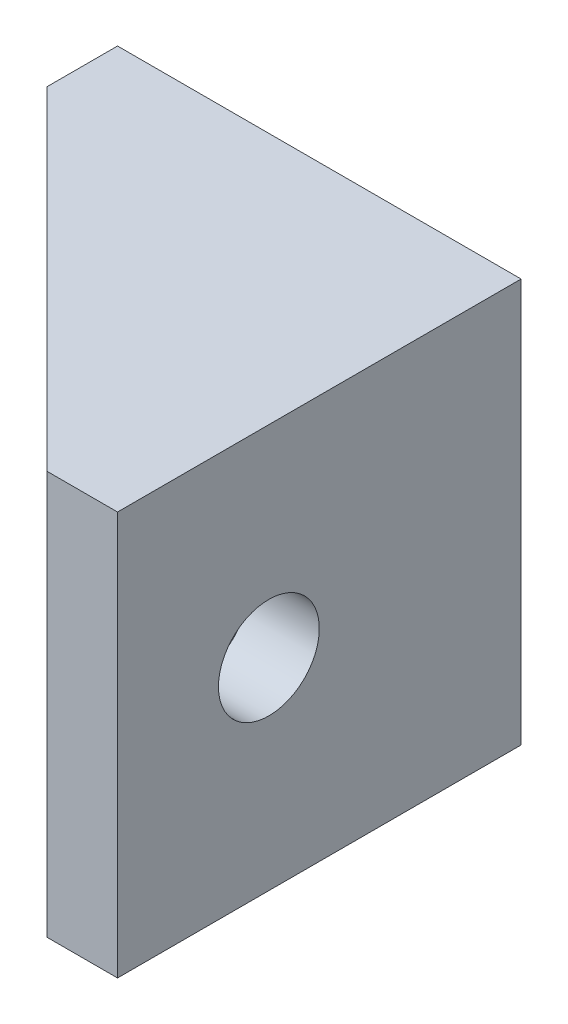
SolidWorks part; units mm, degrees
material "6061 Alloy"
ref_plane "Front Plane" through (0, 0, 0) normal (0, 0, 1) x (1, 0, 0)
ref_plane "Top Plane" through (0, 0, 0) normal (0, 1, 0) x (1, 0, 0)
ref_plane "Right Plane" through (0, 0, 0) normal (1, 0, 0) x (0, 0, -1)
sketch "Sketch1" plane through (0, 0, 0) normal (0, 1, 0) x (1, 0, 0)
  line L1 (-20, 20) -> (0, 20)
  line L2 (-20, 20) -> (-20, 0)
  line L3 (-20, 0) -> (0, 0)
  line L4 (0, 20) -> (0, 0)
  dimension "D1" = 20
extrude "Boss-Extrude1" add sketch "Sketch1" along normal blind 20
sketch "Sketch2" plane through (-20, 0, 0) normal (-1, 0, 0) x (0, 0, 1)
  line L0 (-20, 20) -> (0, 20) construction
  line L1 (-16.5, 18) -> (0, 18)
  line L2 (-16.5, 18) -> (-16.5, 2)
  line L3 (-16.5, 2) -> (0, 2)
  line L4 (0, 18) -> (0, 2)
  line L5 (-20, 0) -> (0, 0) construction
  line L6 (-20, 20) -> (-20, 0) construction
  line L7 (0, 20) -> (0, 0) construction
  dimension "D1" = 2
  dimension "D2" = 2
  dimension "D3" = 3.5
extrude "Cut-Extrude1" cut sketch "Sketch2" against normal blind 16.5
sketch "Sketch3" plane through (0, 18, 0) normal (0, -1, 0) x (-1, 0, 0)
  line L0 (20, 16.5) -> (3.5, 0)
extrude "Cut-Extrude2" cut sketch "Sketch3" against normal through all both and the other way through all
sketch "Sketch4" plane through (-3.5, 0, 0) normal (-1, 0, 0) x (0, 0, 1)
  line L2 (0, 10) -> (-20, 10) construction
  line L3 (0, 2) -> (0, 18) construction
  line L4 (-20, 20) -> (-20, 0) construction
  circle A0 centre (-7.5, 10) radius 2.5
  dimension "D1" = 5
  dimension "D2" = 7.5
extrude "Cut-Extrude3" cut sketch "Sketch4" against normal through all both
sketch "Sketch5" plane through (0, 0, -16.5) normal (0, 0, 1) x (1, 0, 0)
  line L0 (-20, 10) -> (0, 10) construction
  line L1 (-20, 18) -> (-20, 2) construction
  line L2 (0, 20) -> (0, 0) construction
  circle A0 centre (-12.5, 10) radius 2.5
  dimension "D1" = 5
  dimension "D2" = 7.5
extrude "Cut-Extrude4" cut sketch "Sketch5" against normal through all both
